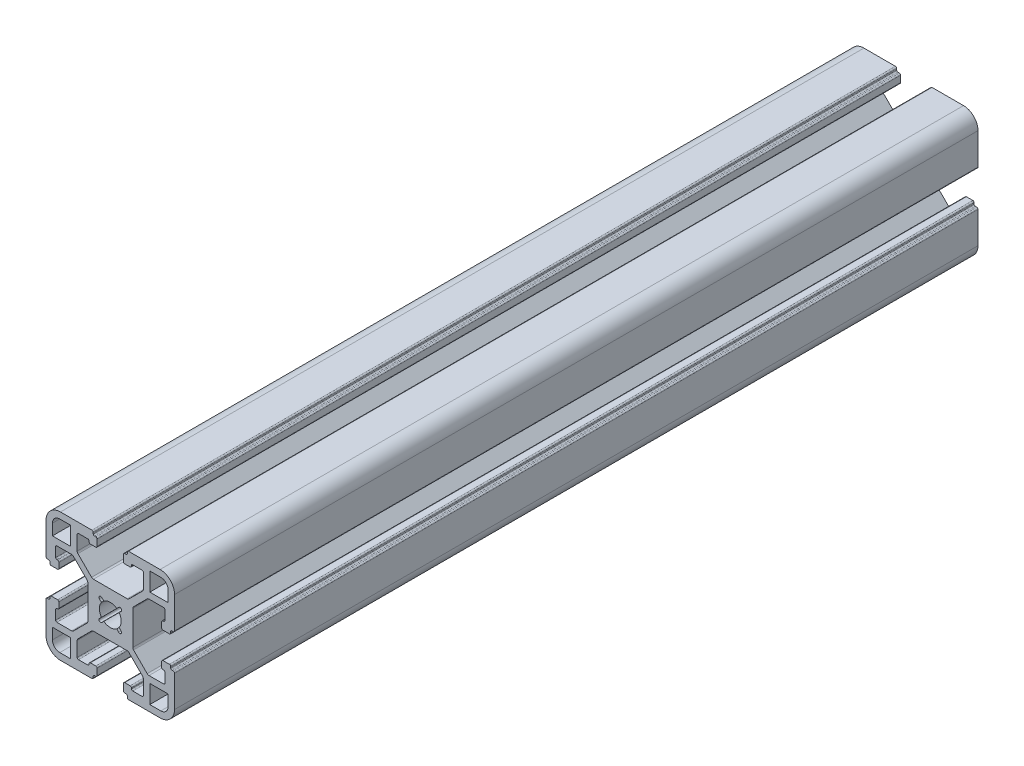
SolidWorks part; units mm, degrees
ref_plane "前视基准面" through (0, 0, 0) normal (0, 0, 1) x (1, 0, 0)
ref_plane "上视基准面" through (0, 0, 0) normal (0, 1, 0) x (1, 0, 0)
ref_plane "右视基准面" through (0, 0, 0) normal (1, 0, 0) x (0, 0, -1)
other "Configuration Table"
ref_plane "Plane1" through (0, 0, 25) normal (0, 0, 1) x (1, 0, 0)
sketch "Sketch1" plane through (0, 0, 25) normal (0, 0, 1) x (1, 0, 0)
  line L0 (18, 15.72) -> (18, 12.3)
  line L1 (18, 12.3) -> (12.3, 12.3)
  line L2 (12.3, 12.3) -> (12.3, 18)
  line L3 (12.3, 18) -> (15.72, 18)
  line L4 (-18, -15.72) -> (-18, -12.3)
  line L5 (-18, -12.3) -> (-12.3, -12.3)
  line L6 (-12.3, -12.3) -> (-12.3, -18)
  line L7 (-12.3, -18) -> (-15.72, -18)
  line L8 (-15.5, -20) -> (-5.7, -20)
  line L9 (-5.3, -19.6) -> (-5.3, -19.2)
  line L10 (-4.9, -18.8) -> (-4.5, -18.8)
  line L11 (-4.1, -18.4) -> (-4.1, -16.4)
  line L12 (-4.5, -16) -> (-6.18, -16)
  line L13 (-6.58, -16.4) -> (-6.58, -16.6)
  line L14 (-6.98, -17) -> (-9.9, -17)
  line L15 (-10.3, -16.6) -> (-10.3, -12.0456)
  line L16 (-10.0657, -11.4799) -> (-5.8201, -7.2343)
  line L17 (-5.2544, -7) -> (5.2544, -7)
  line L18 (5.8201, -7.2343) -> (10.0657, -11.4799)
  line L19 (10.3, -12.0456) -> (10.3, -16.6)
  line L20 (9.9, -17) -> (6.98, -17)
  line L21 (6.58, -16.6) -> (6.58, -16.4)
  line L22 (6.18, -16) -> (4.5, -16)
  line L23 (4.1, -16.4) -> (4.1, -18.4)
  line L24 (4.5, -18.8) -> (4.9, -18.8)
  line L25 (5.3, -19.2) -> (5.3, -19.6)
  line L26 (5.7, -20) -> (15.5, -20)
  line L27 (20, -15.5) -> (20, -5.7)
  line L28 (19.6, -5.3) -> (19.2, -5.3)
  line L29 (18.8, -4.9) -> (18.8, -4.5)
  line L30 (18.4, -4.1) -> (16.4, -4.1)
  line L31 (16, -4.5) -> (16, -6.18)
  line L32 (16.4, -6.58) -> (16.6, -6.58)
  line L33 (17, -6.98) -> (17, -9.9)
  line L34 (16.6, -10.3) -> (12.0456, -10.3)
  line L35 (11.4799, -10.0657) -> (7.2343, -5.8201)
  line L36 (7, -5.2544) -> (7, 5.2544)
  line L37 (7.2343, 5.8201) -> (11.4799, 10.0657)
  line L38 (12.0456, 10.3) -> (16.6, 10.3)
  line L39 (17, 9.9) -> (17, 6.98)
  line L40 (16.6, 6.58) -> (16.4, 6.58)
  line L41 (16, 6.18) -> (16, 4.5)
  line L42 (16.4, 4.1) -> (18.4, 4.1)
  line L43 (18.8, 4.5) -> (18.8, 4.9)
  line L44 (19.2, 5.3) -> (19.6, 5.3)
  line L45 (20, 5.7) -> (20, 15.5)
  line L46 (15.5, 20) -> (5.7, 20)
  line L47 (5.3, 19.6) -> (5.3, 19.2)
  line L48 (4.9, 18.8) -> (4.5, 18.8)
  line L49 (4.1, 18.4) -> (4.1, 16.4)
  line L50 (4.5, 16) -> (6.18, 16)
  line L51 (6.58, 16.4) -> (6.58, 16.6)
  line L52 (6.98, 17) -> (9.9, 17)
  line L53 (10.3, 16.6) -> (10.3, 12.0456)
  line L54 (10.0657, 11.4799) -> (5.8201, 7.2343)
  line L55 (5.2544, 7) -> (-5.2544, 7)
  line L56 (-5.8201, 7.2343) -> (-10.0657, 11.4799)
  line L57 (-10.3, 12.0456) -> (-10.3, 16.6)
  line L58 (-9.9, 17) -> (-6.98, 17)
  line L59 (-6.58, 16.6) -> (-6.58, 16.4)
  line L60 (-6.18, 16) -> (-4.5, 16)
  line L61 (-4.1, 16.4) -> (-4.1, 18.4)
  line L62 (-4.5, 18.8) -> (-4.9, 18.8)
  line L63 (-5.3, 19.2) -> (-5.3, 19.6)
  line L64 (-5.7, 20) -> (-15.5, 20)
  line L65 (-20, 15.5) -> (-20, 5.7)
  line L66 (-19.6, 5.3) -> (-19.2, 5.3)
  line L67 (-18.8, 4.9) -> (-18.8, 4.5)
  line L68 (-18.4, 4.1) -> (-16.4, 4.1)
  line L69 (-16, 4.5) -> (-16, 6.18)
  line L70 (-16.4, 6.58) -> (-16.6, 6.58)
  line L71 (-17, 6.98) -> (-17, 9.9)
  line L72 (-16.6, 10.3) -> (-12.0456, 10.3)
  line L73 (-11.4799, 10.0657) -> (-7.2343, 5.8201)
  line L74 (-7, 5.2544) -> (-7, -5.2544)
  line L75 (-7.2343, -5.8201) -> (-11.4799, -10.0657)
  line L76 (-12.0456, -10.3) -> (-16.6, -10.3)
  line L77 (-17, -9.9) -> (-17, -6.98)
  line L78 (-16.6, -6.58) -> (-16.4, -6.58)
  line L79 (-16, -6.18) -> (-16, -4.5)
  line L80 (-16.4, -4.1) -> (-18.4, -4.1)
  line L81 (-18.8, -4.5) -> (-18.8, -4.9)
  line L82 (-19.2, -5.3) -> (-19.6, -5.3)
  line L83 (-20, -5.7) -> (-20, -15.5)
  line L84 (2.0101, 2.7422) -> (2.6338, 3.3658)
  line L85 (3.3658, 2.6338) -> (2.7422, 2.0101)
  line L86 (2.7422, -2.0101) -> (3.3658, -2.6338)
  line L87 (2.6338, -3.3658) -> (2.0101, -2.7422)
  line L88 (-2.0101, -2.7422) -> (-2.6338, -3.3658)
  line L89 (-3.3658, -2.6338) -> (-2.7422, -2.0101)
  line L90 (-2.7422, 2.0101) -> (-3.3658, 2.6338)
  line L91 (-2.6338, 3.3658) -> (-2.0101, 2.7422)
  line L92 (15.72, -18) -> (12.3, -18)
  line L93 (12.3, -18) -> (12.3, -12.3)
  line L94 (12.3, -12.3) -> (18, -12.3)
  line L95 (18, -12.3) -> (18, -15.72)
  line L96 (-15.72, 18) -> (-12.3, 18)
  line L97 (-12.3, 18) -> (-12.3, 12.3)
  line L98 (-12.3, 12.3) -> (-18, 12.3)
  line L99 (-18, 12.3) -> (-18, 15.72)
  arc A0 (15.72, 18) -> (18, 15.72) centre (15.72, 15.72) cw
  arc A1 (-15.72, -18) -> (-18, -15.72) centre (-15.72, -15.72) cw
  arc A2 (-20, -15.5) -> (-15.5, -20) centre (-15.5, -15.5) ccw
  arc A3 (-5.7, -20) -> (-5.3, -19.6) centre (-5.7, -19.6) ccw
  arc A4 (-5.3, -19.2) -> (-4.9, -18.8) centre (-4.9, -19.2) cw
  arc A5 (-4.5, -18.8) -> (-4.1, -18.4) centre (-4.5, -18.4) ccw
  arc A6 (-4.1, -16.4) -> (-4.5, -16) centre (-4.5, -16.4) ccw
  arc A7 (-6.18, -16) -> (-6.58, -16.4) centre (-6.18, -16.4) ccw
  arc A8 (-6.58, -16.6) -> (-6.98, -17) centre (-6.98, -16.6) cw
  arc A9 (-9.9, -17) -> (-10.3, -16.6) centre (-9.9, -16.6) cw
  arc A10 (-10.3, -12.0456) -> (-10.0657, -11.4799) centre (-9.5, -12.0456) cw
  arc A11 (-5.8201, -7.2343) -> (-5.2544, -7) centre (-5.2544, -7.8) cw
  arc A12 (5.2544, -7) -> (5.8201, -7.2343) centre (5.2544, -7.8) cw
  arc A13 (10.0657, -11.4799) -> (10.3, -12.0456) centre (9.5, -12.0456) cw
  arc A14 (10.3, -16.6) -> (9.9, -17) centre (9.9, -16.6) cw
  arc A15 (6.98, -17) -> (6.58, -16.6) centre (6.98, -16.6) cw
  arc A16 (6.58, -16.4) -> (6.18, -16) centre (6.18, -16.4) ccw
  arc A17 (4.5, -16) -> (4.1, -16.4) centre (4.5, -16.4) ccw
  arc A18 (4.1, -18.4) -> (4.5, -18.8) centre (4.5, -18.4) ccw
  arc A19 (4.9, -18.8) -> (5.3, -19.2) centre (4.9, -19.2) cw
  arc A20 (5.3, -19.6) -> (5.7, -20) centre (5.7, -19.6) ccw
  arc A21 (15.5, -20) -> (20, -15.5) centre (15.5, -15.5) ccw
  arc A22 (20, -5.7) -> (19.6, -5.3) centre (19.6, -5.7) ccw
  arc A23 (19.2, -5.3) -> (18.8, -4.9) centre (19.2, -4.9) cw
  arc A24 (18.8, -4.5) -> (18.4, -4.1) centre (18.4, -4.5) ccw
  arc A25 (16.4, -4.1) -> (16, -4.5) centre (16.4, -4.5) ccw
  arc A26 (16, -6.18) -> (16.4, -6.58) centre (16.4, -6.18) ccw
  arc A27 (16.6, -6.58) -> (17, -6.98) centre (16.6, -6.98) cw
  arc A28 (17, -9.9) -> (16.6, -10.3) centre (16.6, -9.9) cw
  arc A29 (12.0456, -10.3) -> (11.4799, -10.0657) centre (12.0456, -9.5) cw
  arc A30 (7.2343, -5.8201) -> (7, -5.2544) centre (7.8, -5.2544) cw
  arc A31 (7, 5.2544) -> (7.2343, 5.8201) centre (7.8, 5.2544) cw
  arc A32 (11.4799, 10.0657) -> (12.0456, 10.3) centre (12.0456, 9.5) cw
  arc A33 (16.6, 10.3) -> (17, 9.9) centre (16.6, 9.9) cw
  arc A34 (17, 6.98) -> (16.6, 6.58) centre (16.6, 6.98) cw
  arc A35 (16.4, 6.58) -> (16, 6.18) centre (16.4, 6.18) ccw
  arc A36 (16, 4.5) -> (16.4, 4.1) centre (16.4, 4.5) ccw
  arc A37 (18.4, 4.1) -> (18.8, 4.5) centre (18.4, 4.5) ccw
  arc A38 (18.8, 4.9) -> (19.2, 5.3) centre (19.2, 4.9) cw
  arc A39 (19.6, 5.3) -> (20, 5.7) centre (19.6, 5.7) ccw
  arc A40 (20, 15.5) -> (15.5, 20) centre (15.5, 15.5) ccw
  arc A41 (5.7, 20) -> (5.3, 19.6) centre (5.7, 19.6) ccw
  arc A42 (5.3, 19.2) -> (4.9, 18.8) centre (4.9, 19.2) cw
  arc A43 (4.5, 18.8) -> (4.1, 18.4) centre (4.5, 18.4) ccw
  arc A44 (4.1, 16.4) -> (4.5, 16) centre (4.5, 16.4) ccw
  arc A45 (6.18, 16) -> (6.58, 16.4) centre (6.18, 16.4) ccw
  arc A46 (6.58, 16.6) -> (6.98, 17) centre (6.98, 16.6) cw
  arc A47 (9.9, 17) -> (10.3, 16.6) centre (9.9, 16.6) cw
  arc A48 (10.3, 12.0456) -> (10.0657, 11.4799) centre (9.5, 12.0456) cw
  arc A49 (5.8201, 7.2343) -> (5.2544, 7) centre (5.2544, 7.8) cw
  arc A50 (-5.2544, 7) -> (-5.8201, 7.2343) centre (-5.2544, 7.8) cw
  arc A51 (-10.0657, 11.4799) -> (-10.3, 12.0456) centre (-9.5, 12.0456) cw
  arc A52 (-10.3, 16.6) -> (-9.9, 17) centre (-9.9, 16.6) cw
  arc A53 (-6.98, 17) -> (-6.58, 16.6) centre (-6.98, 16.6) cw
  arc A54 (-6.58, 16.4) -> (-6.18, 16) centre (-6.18, 16.4) ccw
  arc A55 (-4.5, 16) -> (-4.1, 16.4) centre (-4.5, 16.4) ccw
  arc A56 (-4.1, 18.4) -> (-4.5, 18.8) centre (-4.5, 18.4) ccw
  arc A57 (-4.9, 18.8) -> (-5.3, 19.2) centre (-4.9, 19.2) cw
  arc A58 (-5.3, 19.6) -> (-5.7, 20) centre (-5.7, 19.6) ccw
  arc A59 (-15.5, 20) -> (-20, 15.5) centre (-15.5, 15.5) ccw
  arc A60 (-20, 5.7) -> (-19.6, 5.3) centre (-19.6, 5.7) ccw
  arc A61 (-19.2, 5.3) -> (-18.8, 4.9) centre (-19.2, 4.9) cw
  arc A62 (-18.8, 4.5) -> (-18.4, 4.1) centre (-18.4, 4.5) ccw
  arc A63 (-16.4, 4.1) -> (-16, 4.5) centre (-16.4, 4.5) ccw
  arc A64 (-16, 6.18) -> (-16.4, 6.58) centre (-16.4, 6.18) ccw
  arc A65 (-16.6, 6.58) -> (-17, 6.98) centre (-16.6, 6.98) cw
  arc A66 (-17, 9.9) -> (-16.6, 10.3) centre (-16.6, 9.9) cw
  arc A67 (-12.0456, 10.3) -> (-11.4799, 10.0657) centre (-12.0456, 9.5) cw
  arc A68 (-7.2343, 5.8201) -> (-7, 5.2544) centre (-7.8, 5.2544) cw
  arc A69 (-7, -5.2544) -> (-7.2343, -5.8201) centre (-7.8, -5.2544) cw
  arc A70 (-11.4799, -10.0657) -> (-12.0456, -10.3) centre (-12.0456, -9.5) cw
  arc A71 (-16.6, -10.3) -> (-17, -9.9) centre (-16.6, -9.9) cw
  arc A72 (-17, -6.98) -> (-16.6, -6.58) centre (-16.6, -6.98) cw
  arc A73 (-16.4, -6.58) -> (-16, -6.18) centre (-16.4, -6.18) ccw
  arc A74 (-16, -4.5) -> (-16.4, -4.1) centre (-16.4, -4.5) ccw
  arc A75 (-18.4, -4.1) -> (-18.8, -4.5) centre (-18.4, -4.5) ccw
  arc A76 (-18.8, -4.9) -> (-19.2, -5.3) centre (-19.2, -4.9) cw
  arc A77 (-19.6, -5.3) -> (-20, -5.7) centre (-19.6, -5.7) ccw
  arc A78 (2.6338, 3.3658) -> (3.3658, 2.6338) centre (2.9998, 2.9998) cw
  arc A79 (2.7422, 2.0101) -> (2.7422, -2.0101) centre (0, 0) cw
  arc A80 (3.3658, -2.6338) -> (2.6338, -3.3658) centre (2.9998, -2.9998) cw
  arc A81 (2.0101, -2.7422) -> (-2.0101, -2.7422) centre (0, 0) cw
  arc A82 (-2.6338, -3.3658) -> (-3.3658, -2.6338) centre (-2.9998, -2.9998) cw
  arc A83 (-2.7422, -2.0101) -> (-2.7422, 2.0101) centre (0, 0) cw
  arc A84 (-3.3658, 2.6338) -> (-2.6338, 3.3658) centre (-2.9998, 2.9998) cw
  arc A85 (-2.0101, 2.7422) -> (2.0101, 2.7422) centre (0, 0) cw
  arc A86 (18, -15.72) -> (15.72, -18) centre (15.72, -15.72) cw
  arc A87 (-18, 15.72) -> (-15.72, 18) centre (-15.72, 15.72) cw
extrude "Boss-Extrude1" add sketch "Sketch1" against normal blind 250
